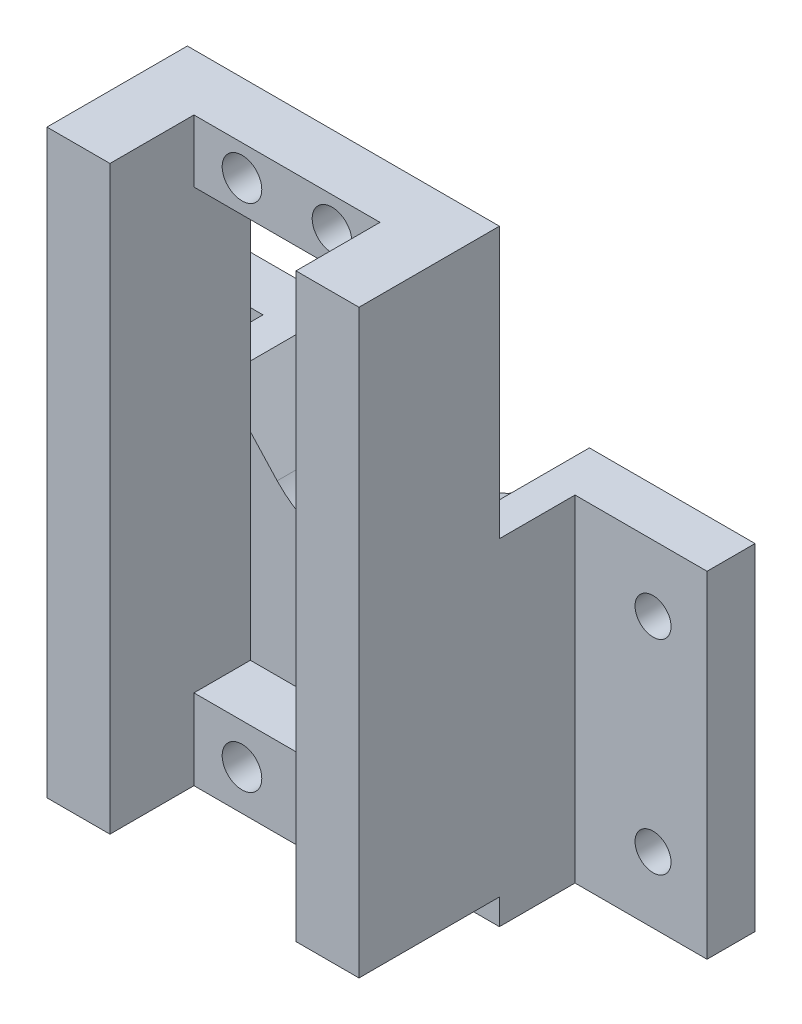
SolidWorks part; units mm, degrees
ref_plane "Płaszczyzna przednia" through (0, 0, 0) normal (0, 0, 1) x (1, 0, 0)
ref_plane "Płaszczyzna górna" through (0, 0, 0) normal (0, 1, 0) x (1, 0, 0)
ref_plane "Płaszczyzna prawa" through (0, 0, 0) normal (1, 0, 0) x (0, 0, -1)
sketch "Szkic1" plane through (0, 0, 0) normal (0, 0, 1) x (1, 0, 0)
  line L0 (-21.9251, -8.5) -> (30.3134, -8.5) construction
  line L1 (-23.7329, 8.5) -> (30.3134, 8.5) construction
  line L2 (-19.5, 12.0712) -> (-19.5, -12.7389) construction
  line L3 (19.5, 11.2609) -> (19.5, -13.2376) construction
  line L5 (-24, 14) -> (24, 14)
  line L6 (-24, 14) -> (-24, -14)
  line L7 (-24, -14) -> (24, -14)
  line L8 (24, 14) -> (24, -14)
  line L9 (-24, 14) -> (24, -14) construction
  line L10 (-24, -14) -> (24, 14) construction
  circle A0 centre (-19.5, 8.5) radius 1.5
  circle A1 centre (-19.5, -8.5) radius 1.5
  circle A2 centre (19.5, -8.5) radius 1.5
  circle A3 centre (19.5, 8.5) radius 1.5
  point P17 (0, 0)
  dimension "D5" = 3
  dimension "D6" = 3
  dimension "D7" = 3
  dimension "D8" = 3
  dimension "D1" = 8.5
  dimension "D2" = 8.5
  dimension "D3" = 19.5
  dimension "D4" = 19.5
  dimension "D9" = 24
  dimension "D10" = 14
extrude "Dodanie-wyciągnięcie1" add sketch "Szkic1" along normal blind 4
sketch "Szkic2" plane through (0, 0, 4) normal (0, 0, 1) x (1, 0, 0)
  line L0 (24, 14) -> (-24, 14) construction
  line L1 (5.5168, 8.9191) -> (10.1962, 14)
  line L2 (0, -2.2) -> (0, 2.2) construction
  line L3 (-5.5168, 8.9191) -> (-10.1962, 14)
  line L4 (-10.1962, 14) -> (10.1962, 14)
  arc A0 (-5.5168, 8.9191) -> (5.5168, 8.9191) centre (0, 14) ccw
  dimension "D1" = 15
extrude "Wytnij-wyciągnięcie1" cut sketch "Szkic2" against normal blind 4
sketch "Szkic3" plane through (0, 0, 4) normal (0, 0, 1) x (1, 0, 0)
  line L0 (-18, -8.5) -> (18, -8.5) construction
  line L2 (-13, -11.85) -> (13, -11.85)
  line L3 (-13, -11.85) -> (-13, -5.15)
  line L4 (-13, -5.15) -> (13, -5.15)
  line L5 (13, -11.85) -> (13, -5.15)
  line L6 (-13, -11.85) -> (13, -5.15) construction
  line L7 (-13, -5.15) -> (13, -11.85) construction
  circle A0 centre (-19.5, -8.5) radius 1.5 construction
  circle A1 centre (19.5, -8.5) radius 1.5 construction
  point P6 (0, -8.5)
  dimension "D1" = 6.7
  dimension "D2" = 26
  dimension "D3" = 5
  dimension "D4" = 5
extrude "Dodanie-wyciągnięcie2" add sketch "Szkic3" along normal blind 11
sketch "Szkic4" plane through (0, 0, 4) normal (0, 0, 1) x (1, 0, 0)
  line L0 (24, 14) -> (10.1962, 14) construction
  line L1 (-13, -5.15) -> (13, -5.15)
  line L2 (-13, -5.15) -> (-13, 14)
  line L3 (-13, 14) -> (-10.1962, 14)
  line L4 (13, -5.15) -> (13, 14)
  line L5 (13, -11.85) -> (13, -5.15) construction
  line L10 (10.1962, 14) -> (13, 14)
  line L12 (5.5168, 8.9191) -> (10.1962, 14)
  line L13 (-10.1962, 14) -> (-5.5168, 8.9191)
  line L14 (5.5168, 8.9191) -> (10.1962, 14)
  line L15 (-10.1962, 14) -> (-5.5168, 8.9191)
  arc A4 (-5.5168, 8.9191) -> (5.5168, 8.9191) centre (0, 14) ccw
  arc A5 (-5.5168, 8.9191) -> (5.5168, 8.9191) centre (0, 14) ccw
  dimension "D1" = 0
  dimension "D2" = 0
extrude "Dodanie-wyciągnięcie3" add sketch "Szkic4" along normal blind 6.3
sketch "Szkic5" plane through (0, 0, 4) normal (0, 0, 1) x (1, 0, 0)
  line L0 (-24, -14) -> (24, -14) construction
  line L1 (-13, -11.85) -> (13, -11.85)
  line L2 (-13, -11.85) -> (-13, -14)
  line L3 (-13, -14) -> (13, -14)
  line L4 (13, -11.85) -> (13, -14)
  line L5 (13, -11.85) -> (13, -5.15) construction
  dimension "D1" = 0
extrude "Dodanie-wyciągnięcie4" add sketch "Szkic5" along normal blind 6.3
sketch "Szkic9" plane through (0, 0, 10.3) normal (0, 0, 1) x (1, 0, 0)
  line L0 (-13, -5.15) -> (-13, 36.55)
  line L1 (13, -5.15) -> (13, 36.55)
  line L2 (13, 36.55) -> (-13, 36.55)
  line L3 (-13, -11.85) -> (13, -11.85) construction
  line L4 (-7.75, -5.15) -> (-7.75, 31.35)
  line L5 (-13, -5.15) -> (13, -5.15) construction
  line L6 (-7.75, 31.35) -> (7.75, 31.35)
  line L7 (7.75, 31.35) -> (7.75, -5.15)
  line L8 (-13, -5.15) -> (-7.75, -5.15)
  line L9 (7.75, -5.15) -> (13, -5.15)
  dimension "D1" = 48.4
  dimension "D2" = 36.5
  dimension "D3" = 15.5
  dimension "D4" = 5.25
  dimension "D5" = 5.25
extrude "Dodanie-wyciągnięcie7" add sketch "Szkic9" along normal up to surface (4.7 mm away) contours L4 L6 L7 L9 L1 L2 L0 L8 up to face at (0, -8.5, 15)
sketch "Szkic10" plane through (0, 0, 15) normal (0, 0, 1) x (1, 0, 0)
  line L0 (-7.6529, -8.5) -> (8.6598, -8.5) construction
  line L1 (-13, -11.85) -> (13, -11.85) construction
  line L2 (0, 0) -> (0, -16.857) construction
  circle A0 centre (-3.75, -8.5) radius 1.65
  circle A1 centre (3.75, -8.5) radius 1.65
  circle A2 centre (-3.75, 34) radius 1.65
  circle A3 centre (3.75, 34) radius 1.65
  dimension "D3" = 3.3
  dimension "D4" = 3.3
  dimension "D7" = 3.3
  dimension "D8" = 3.3
  dimension "D1" = 3.35
  dimension "D2" = 3.75
  dimension "D5" = 3.75
  dimension "D6" = 42.5
extrude "Wytnij-wyciągnięcie2" cut sketch "Szkic10" against normal up to surface (15 mm away) up to face at (0, 5.4274, 0)
sketch "Szkic12" plane through (0, 0, 15) normal (0, 0, 1) x (1, 0, 0)
  line L0 (-7.75, -5.15) -> (-7.75, -11.85) construction
  line L1 (13, -11.85) -> (-13, -11.85) construction
  line L2 (7.75, -5.15) -> (7.75, -11.85) construction
  line L4 (-13, 36.55) -> (-7.75, 36.55)
  line L5 (-13, 36.55) -> (-13, -11.85)
  line L6 (-13, -11.85) -> (-7.75, -11.85)
  line L7 (-7.75, 36.55) -> (-7.75, -11.85)
  line L8 (13, 36.55) -> (7.75, 36.55)
  line L9 (13, 36.55) -> (13, -11.85)
  line L10 (13, -11.85) -> (7.75, -11.85)
  line L11 (7.75, 36.55) -> (7.75, -11.85)
  line L12 (-13, 36.55) -> (-7.75, 36.55)
  line L13 (-13, 36.55) -> (-13, -11.85)
  line L14 (-13, -11.85) -> (-7.75, -11.85)
  line L15 (-7.75, 36.55) -> (-7.75, -11.85)
  line L16 (13, 36.55) -> (7.75, 36.55)
  line L17 (13, 36.55) -> (13, -11.85)
  line L18 (13, -11.85) -> (7.75, -11.85)
  line L19 (7.75, 36.55) -> (7.75, -11.85)
  line M5 (13, 36.55) -> (-13, 36.55)
  line M6 (-13, 36.55) -> (-13, -11.85)
  line M7 (-13, -11.85) -> (13, -11.85)
  line M8 (13, -11.85) -> (13, 36.55)
  line M10 (-7.75, -5.15) -> (-7.75, 31.35)
  line M12 (7.75, 31.35) -> (7.75, -5.15)
extrude "Dodanie-wyciągnięcie8" add sketch "Szkic12" along normal blind 7 contours L7 M5 M6 M7 M10 | L11 M5 M12 M7 M8
sketch "Szkic14" plane through (0, 0, 0) normal (0, 0, -1) x (-1, 0, 0)
  line L1 (-3.75, -4.4585) -> (-7.25, -6.4793)
  line L2 (-7.25, -6.4793) -> (-7.25, -10.5207)
  line L3 (-7.25, -10.5207) -> (-3.75, -12.5415)
  line L4 (-3.75, -12.5415) -> (-0.25, -10.5207)
  line L5 (-0.25, -10.5207) -> (-0.25, -6.4793)
  line L6 (-0.25, -6.4793) -> (-3.75, -4.4585)
  line L7 (3.75, -4.4585) -> (0.25, -6.4793)
  line L8 (0.25, -6.4793) -> (0.25, -10.5207)
  line L9 (0.25, -10.5207) -> (3.75, -12.5415)
  line L10 (3.75, -12.5415) -> (7.25, -10.5207)
  line L11 (7.25, -10.5207) -> (7.25, -6.4793)
  line L12 (7.25, -6.4793) -> (3.75, -4.4585)
  circle A0 centre (-3.75, -8.5) radius 3.5 construction
  circle A1 centre (3.75, -8.5) radius 3.5 construction
  dimension "D1" = 3.5
  dimension "D2" = 3.5
extrude "Wytnij-wyciągnięcie3" cut sketch "Szkic14" against normal blind 7
